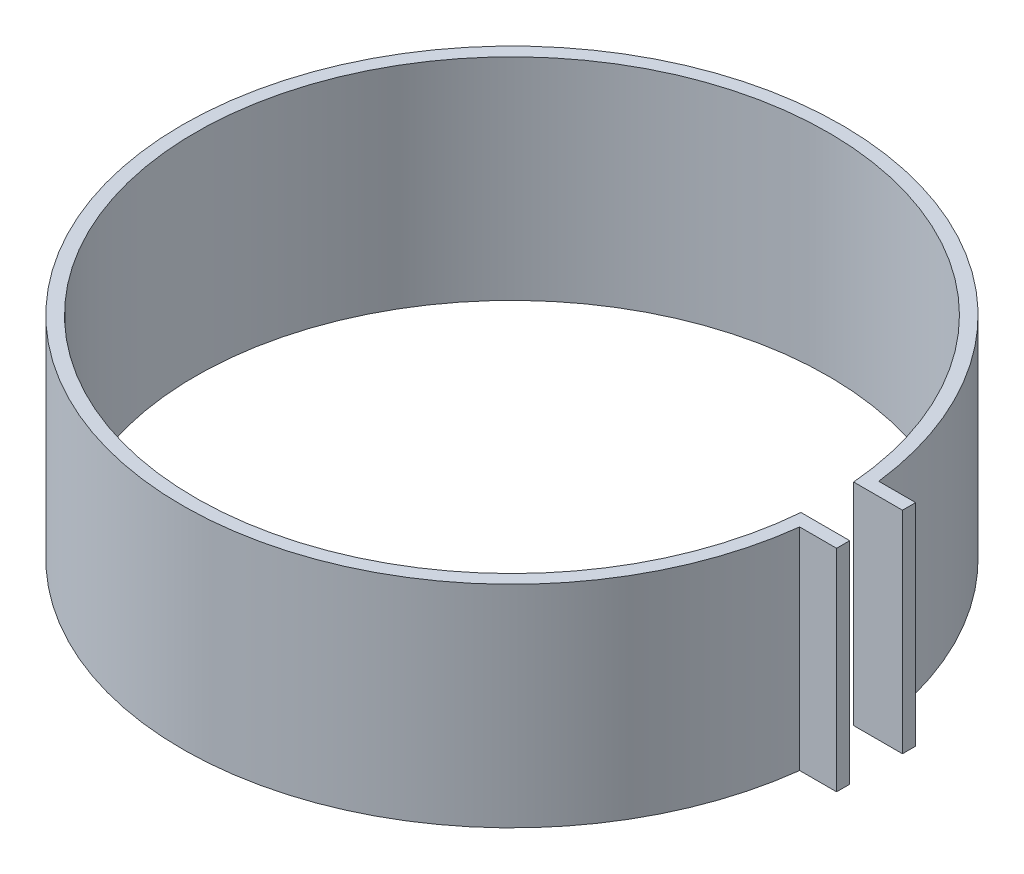
SolidWorks part; units mm, degrees
ref_plane "Front" through (0, 0, 0) normal (0, 0, 1) x (1, 0, 0)
ref_plane "Top" through (0, 0, 0) normal (0, 1, 0) x (1, 0, 0)
ref_plane "Right" through (0, 0, 0) normal (1, 0, 0) x (0, 0, -1)
sketch "Sketch2" plane through (0, 0, 0) normal (0, 1, 0) x (1, 0, 0)
  line L0 (76.0008, 0) -> (87.691, 0) construction
  line L1 (78.801, -6.35) -> (87.691, -6.35)
  line L2 (78.801, 6.35) -> (87.691, 6.35)
  line L3 (76.0008, 6.35) -> (87.691, 6.35) construction
  line L4 (76.0008, -6.35) -> (87.691, -6.35) construction
  line L5 (78.801, -6.35) -> (75.935, -6.35)
  line L6 (78.801, 6.35) -> (75.935, 6.35)
  line L7 (78.8014, 9.525) -> (87.691, 9.525)
  line L9 (87.691, 9.525) -> (87.691, 6.35)
  line L11 (78.8014, -9.525) -> (87.691, -9.525)
  line L12 (87.691, -6.35) -> (87.691, -9.525)
  line L13 (78.801, -9.525) -> (75.935, -9.525) construction
  line L14 (78.801, 9.525) -> (75.935, 9.525) construction
  line L15 (78.801, 9.525) -> (87.691, 9.525) construction
  line L16 (78.801, -9.525) -> (87.691, -9.525) construction
  arc A0 (75.935, 6.35) -> (75.935, -6.35) centre (0, 0) ccw
  arc A1 (78.8014, 9.525) -> (78.8014, -9.525) centre (0, 0) ccw
  circle A2 centre (0, 0) radius 79.375 construction
  circle A3 centre (0, 0) radius 76.2 construction
  dimension "D1" = 152.4
  dimension "D6" = 8.89
  dimension "D7" = 3.175
  dimension "D3" = 6.35
  dimension "D4" = 6.35
  dimension "D2" = 3.175
  dimension "D5" = 3.175
extrude "Boss-Extrude1" add sketch "Sketch2" along normal blind 50.8
